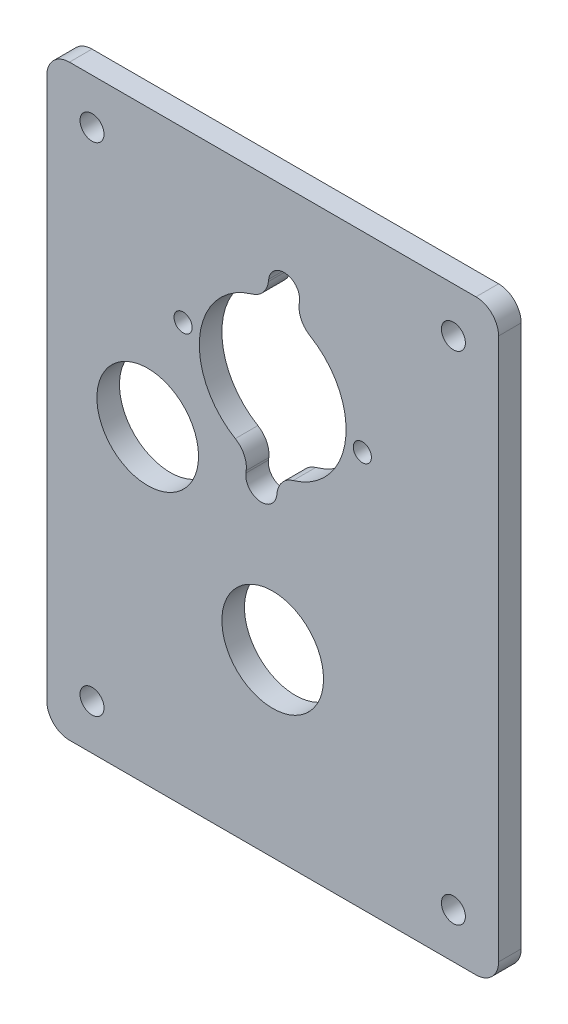
SolidWorks part; units mm, degrees
ref_plane "Front Plane" through (0, 0, 0) normal (0, 0, 1) x (1, 0, 0)
ref_plane "Top Plane" through (0, 0, 0) normal (0, 1, 0) x (1, 0, 0)
ref_plane "Right Plane" through (0, 0, 0) normal (1, 0, 0) x (0, 0, -1)
sketch "Sketch1" plane through (0, 0, 0) normal (0, 0, 1) x (1, 0, 0)
  line L0 (0, -31.9522) -> (0, 31.9522) construction
  line L1 (-63.5, -82.55) -> (63.5, -82.55)
  line L2 (-63.5, -82.55) -> (-63.5, 82.55)
  line L3 (-63.5, 82.55) -> (63.5, 82.55)
  line L4 (63.5, -82.55) -> (63.5, 82.55)
  line L5 (-63.5, -82.55) -> (63.5, 82.55) construction
  line L6 (-63.5, 82.55) -> (63.5, -82.55) construction
  line L7 (-50.8, -69.85) -> (50.8, -69.85) construction
  line L8 (-50.8, -69.85) -> (-50.8, 69.85) construction
  line L9 (-50.8, 69.85) -> (50.8, 69.85) construction
  line L10 (50.8, -69.85) -> (50.8, 69.85) construction
  line L11 (-50.8, -69.85) -> (50.8, 69.85) construction
  line L12 (-50.8, 69.85) -> (50.8, -69.85) construction
  line L13 (-7.5346, 7.3052) -> (-7.4549, 7.9325)
  line L14 (3.2006, 57.1497) -> (25.1975, 28.7516) construction
  line L15 (3.2006, 57.1497) -> (-25.1975, 35.1528) construction
  line L16 (-25.1975, 35.1528) -> (-3.2006, 6.7547) construction
  line L17 (25.1975, 28.7516) -> (-3.2006, 6.7547) construction
  line L18 (3.2006, 57.1497) -> (-3.2006, 6.7547) construction
  line L19 (-25.1975, 35.1528) -> (25.1975, 28.7516) construction
  line L20 (1.1334, 6.2042) -> (1.2131, 6.8315)
  line L21 (7.5346, 56.5992) -> (7.4549, 55.9719)
  line L22 (-1.1334, 57.7002) -> (-1.2131, 57.0729)
  line L23 (0, 31.9522) -> (-35.1409, 4.7324) construction
  circle A0 centre (-50.8, 69.85) radius 3.3734
  circle A1 centre (50.8, 69.85) radius 3.3734
  circle A2 centre (50.8, -69.85) radius 3.3734
  circle A3 centre (-50.8, -69.85) radius 3.3734
  arc A4 (-5.7448, 51.774) -> (-10.518, 14.1961) centre (0, 31.9522) ccw
  circle A5 centre (0, -31.9522) radius 14.2875
  circle A6 centre (-35.1409, 4.7324) radius 14.2875
  circle A7 centre (25.1975, 28.7516) radius 2.5527
  arc A8 (-7.5346, 7.3052) -> (1.1334, 6.2042) centre (-3.2006, 6.7547) ccw
  arc A9 (7.5346, 56.5992) -> (-1.1334, 57.7002) centre (3.2006, 57.1497) ccw
  circle A10 centre (-25.1975, 35.1528) radius 2.5527
  arc A11 (5.7448, 12.1304) -> (10.518, 49.7083) centre (0, 31.9522) ccw
  arc A12 (-1.2131, 57.0729) -> (-5.7448, 51.774) centre (-7.5125, 57.873) cw
  arc A13 (7.4549, 55.9719) -> (10.518, 49.7083) centre (13.7543, 55.1717) ccw
  arc A14 (1.2131, 6.8315) -> (5.7448, 12.1304) centre (7.5125, 6.0314) cw
  arc A15 (-7.4549, 7.9325) -> (-10.518, 14.1961) centre (-13.7543, 8.7327) ccw
  point P0 (0, 0)
  point P6 (0, 0)
  point P40 (1.7924, 11.3927)
  point P43 (-14.1991, 20.9537)
  dimension "D5" = 6.7469
  dimension "D6" = 28.575
  dimension "D7" = 41.275
  dimension "D12" = 5.1054
  dimension "D13" = 8.7376
  dimension "D14" = 6.35
  dimension "D1" = 139.7
  dimension "D2" = 101.6
  dimension "D3" = 165.1
  dimension "D4" = 127
  dimension "D8" = 50.8
  dimension "D9" = 44.45
  dimension "D10" = 35.1409
  dimension "D11" = 50.8
extrude "Boss-Extrude1" add sketch "Sketch1" along normal blind 6.35
fillet "Fillet1" radius 6.35 4 edges at (-63.5, 82.55, 3.175) (-63.5, -82.55, 3.175) (63.5, -82.55, 3.175) (63.5, 82.55, 3.175)
